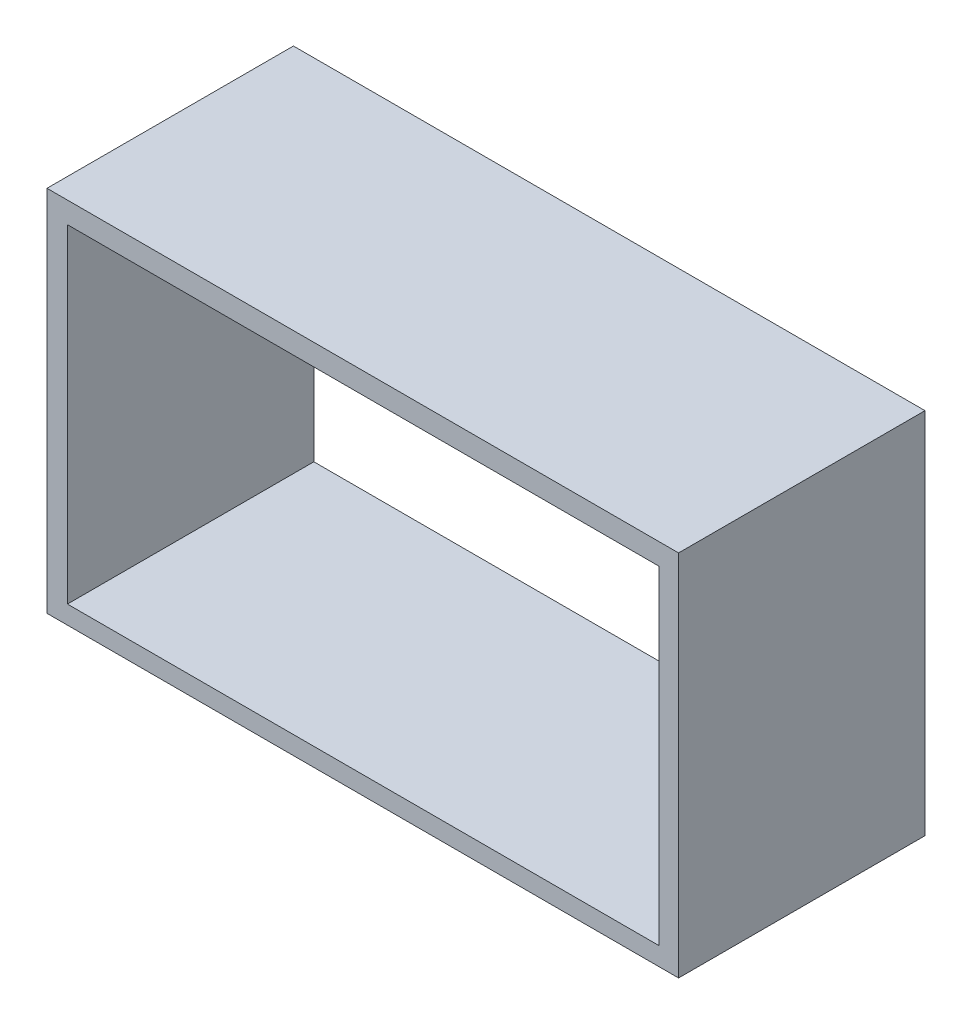
SolidWorks part; units mm, degrees
ref_plane "Front Plane" through (0, 0, 0) normal (0, 0, 1) x (1, 0, 0)
ref_plane "Top Plane" through (0, 0, 0) normal (0, 1, 0) x (1, 0, 0)
ref_plane "Right Plane" through (0, 0, 0) normal (1, 0, 0) x (0, 0, -1)
sketch "Sketch1" plane through (0, 0, 0) normal (0, 0, 1) x (1, 0, 0)
  line L1 (-9.1119, 11.9988) -> (26.8881, 11.9988)
  line L2 (-9.1119, 11.9988) -> (-9.1119, -8.0012)
  line L3 (-9.1119, -8.0012) -> (26.8881, -8.0012)
  line L4 (26.8881, 11.9988) -> (26.8881, -8.0012)
  line L5 (-10.3556, 13.2952) -> (28.0889, 13.2952)
  line L6 (-10.3556, 13.2952) -> (-10.3556, -9.113)
  line L7 (-10.3556, -9.113) -> (28.0889, -9.113)
  line L8 (28.0889, 13.2952) -> (28.0889, -9.113)
  dimension "D1" = 36
  dimension "D2" = 20
  dimension "D3" = 38.4446
  dimension "D4" = 22.4081
extrude "Boss-Extrude4" add sketch "Sketch1" along normal blind 15
